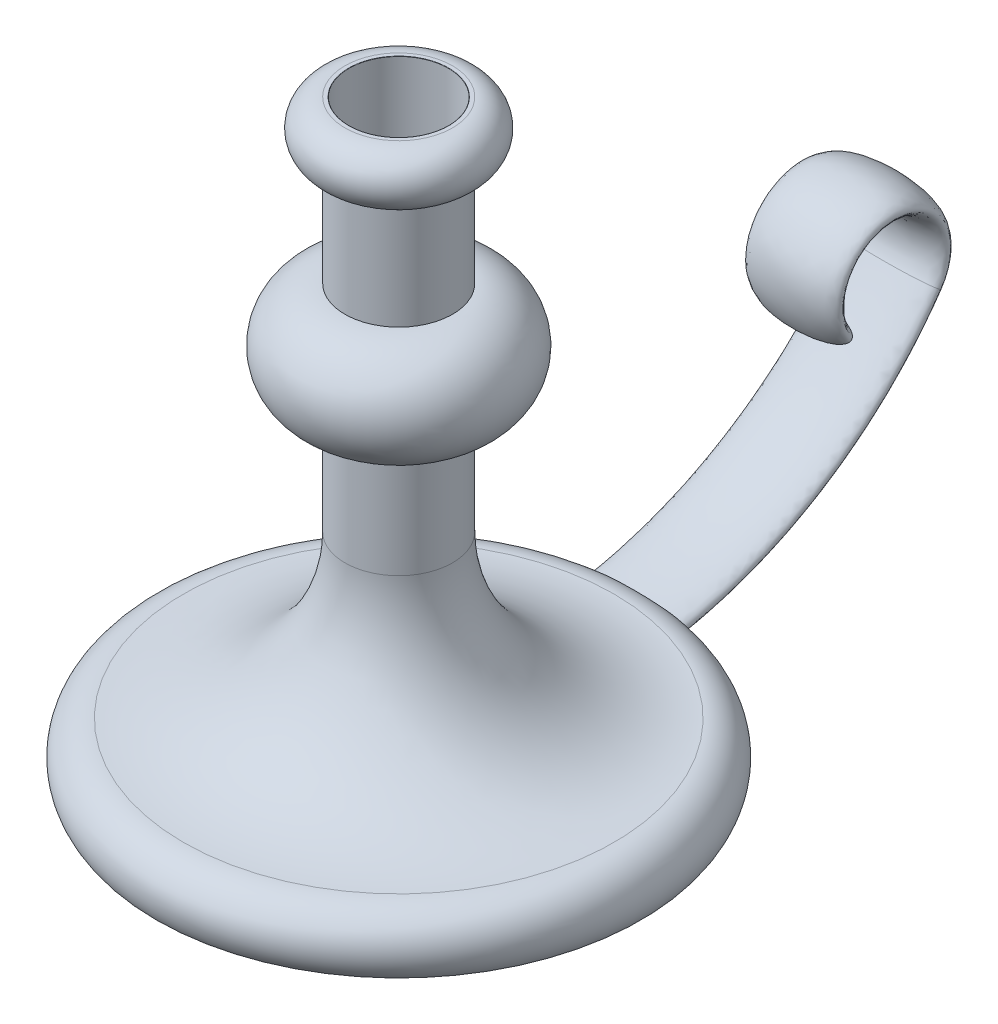
SolidWorks part; units mm, degrees
ref_plane "Front Plane" through (0, 0, 0) normal (0, 0, 1) x (1, 0, 0)
ref_plane "Top Plane" through (0, 0, 0) normal (0, 1, 0) x (1, 0, 0)
ref_plane "Right Plane" through (0, 0, 0) normal (1, 0, 0) x (0, 0, -1)
sketch "Sketch1" plane through (0, 0, 0) normal (0, 0, 1) x (1, 0, 0)
  line L0 (0, 0) -> (0, 5588)
  line L1 (0, 5588) -> (508, 5588)
  line L2 (0, 0) -> (2286, 0)
  line L3 (507.9999, 5080) -> (507.9999, 4064)
  line L4 (507.9999, 3048) -> (507.9999, 2032)
  arc A0 (508, 5588) -> (507.9999, 5080) centre (508, 5334) cw
  arc A1 (507.9999, 3048) -> (507.9999, 4064) centre (507.9999, 3556) ccw
  arc A2 (507.9999, 2032) -> (2032, 508) centre (2031.9999, 2032) ccw
  arc A3 (2032, 508) -> (2286, 0) centre (2032, 190.5) cw
  dimension "D4" = 254
  dimension "D6" = 508
  dimension "D7" = 1524
  dimension "D8" = 317.5
  dimension "D1" = 5588
  dimension "D2" = 508
  dimension "D3" = 2286
  dimension "D5" = 1016
  dimension "D9" = 2032
revolve "Revolve2" add sketch "Sketch1" angle 360 about L0
sketch "Sketch4" plane through (0, 5588, 0) normal (0, 1, 0) x (1, 0, 0)
  circle A0 centre (0, 0) radius 469.9
extrude "Cut-Extrude1" cut sketch "Sketch4" against normal blind 5033.264
fillet "Fillet2" radius 2.54 1 edges at (0, 5588, 469.9)
sketch "Sketch6" plane through (0, 0, 0) normal (1, 0, 0) x (0, 0, -1)
  line L0 (0, 254) -> (1524, 254)
  line L1 (0, 5776.8641) -> (0, 4448.2717) construction
  line L2 (-2286, 0) -> (2286, 0) construction
  arc A0 (1524, 254) -> (4663.2386, 1905) centre (1524, 4064) ccw
  arc A1 (4663.2386, 1905) -> (3826.1083, 1905) centre (4244.6735, 2192.8667) ccw
  dimension "D2" = 3810
  dimension "D4" = 508
  dimension "D1" = 1524
  dimension "D3" = 1651
  dimension "D5" = 254
sketch "Sketch7" plane through (0, 0, 0) normal (0, 0, 1) x (1, 0, 0)
  line L0 (0, 254) -> (0, 1905) construction
  ellipse E0 centre (0, 254) end of major axis (444.5, 254) minor radius 127
  point P1 (0, 0)
  dimension "D1" = 254
  dimension "D2" = 889
sweep "Sweep1" add profiles "Sketch7" path "Sketch6"
